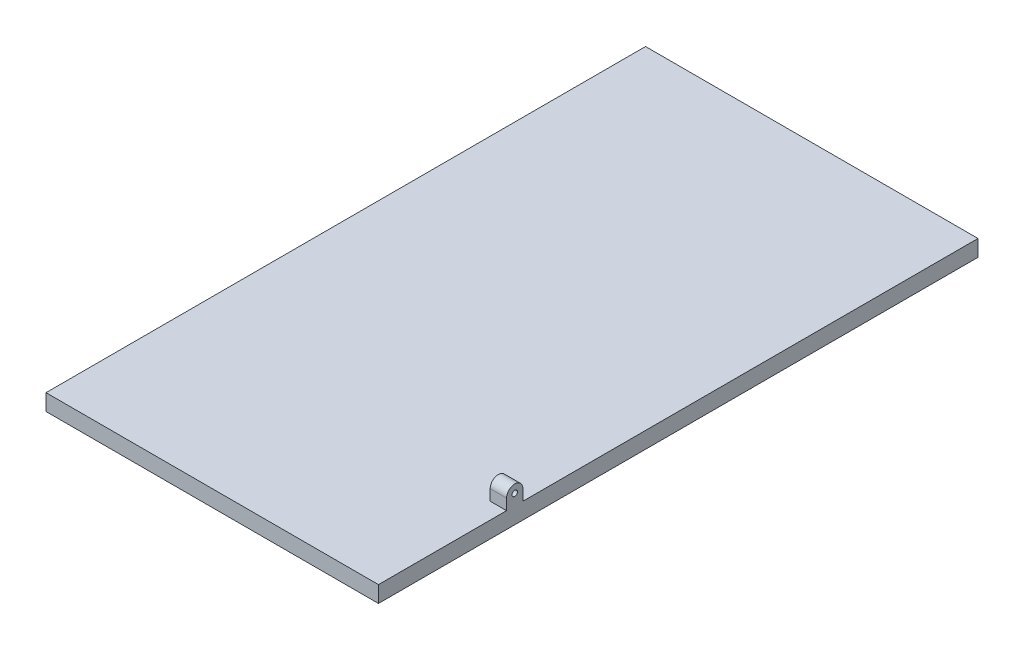
SolidWorks part; units mm, degrees
material "Acrilico TEC"
ref_plane "Front Plane" through (0, 0, 0) normal (0, 0, 1) x (1, 0, 0)
ref_plane "Top Plane" through (0, 0, 0) normal (0, 1, 0) x (1, 0, 0)
ref_plane "Right Plane" through (0, 0, 0) normal (1, 0, 0) x (0, 0, -1)
sketch "Sketch1" plane through (0, 0, 0) normal (0, 1, 0) x (1, 0, 0)
  line L1 (0, 0) -> (61, 0)
  line L2 (0, 0) -> (0, 100)
  line L3 (0, 100) -> (61, 100)
  line L4 (61, 0) -> (61, 100)
  dimension "D1" = 61
  dimension "D2" = 100
extrude "Boss-Extrude1" add sketch "Sketch1" along normal blind 3
sketch "Sketch4" plane through (0, 0, 0) normal (0, 0, 1) x (1, 0, 0)
  line L1 (0, 0) -> (61, 0)
  line L2 (0, 0) -> (0, 3)
  line L3 (0, 3) -> (61, 3)
  line L4 (61, 0) -> (61, 3)
extrude "Boss-Extrude3" add sketch "Sketch4" along normal blind 10
sketch "Sketch8" plane through (61, 0, 0) normal (1, 0, 0) x (0, 0, -1)
  line L9 (13.5, 3) -> (16.5, 3)
  line L10 (16.5, 3) -> (16.5, 5)
  line L12 (13.5, 3) -> (13.5, 5)
  circle A2 centre (15, 5) radius 0.5
  arc A3 (13.5, 5) -> (16.5, 5) centre (15, 5) cw
  dimension "D1" = 3
  dimension "D2" = 15
  dimension "D3" = 1
  dimension "D5" = 1.5
  dimension "D4" = 2
  dimension "D6" = 3
extrude "Boss-Extrude6" add sketch "Sketch8" against normal blind 3
